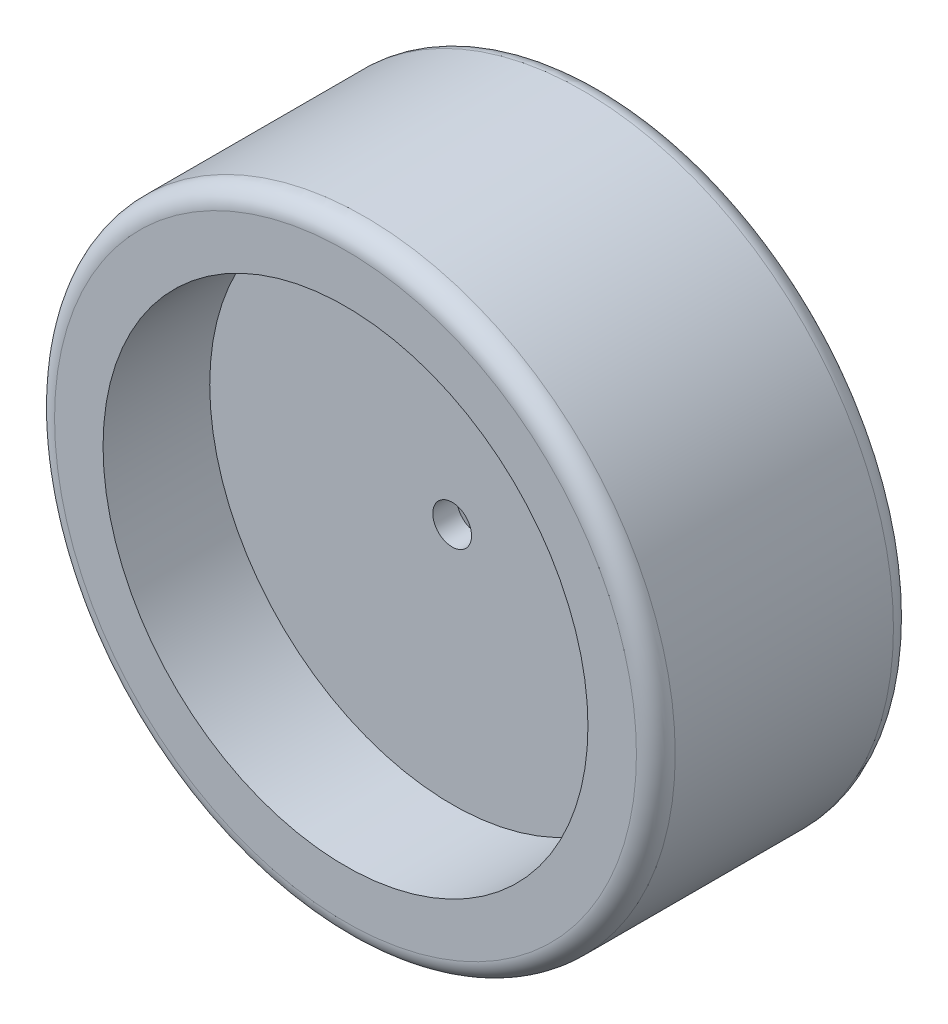
SolidWorks part; units mm, degrees
ref_plane "前视基准面" through (0, 0, 0) normal (0, 0, 1) x (1, 0, 0)
ref_plane "上视基准面" through (0, 0, 0) normal (0, 1, 0) x (1, 0, 0)
ref_plane "右视基准面" through (0, 0, 0) normal (1, 0, 0) x (0, 0, -1)
sketch "草图1" plane through (0, 0, 0) normal (0, 0, 1) x (1, 0, 0)
  line L1 (3.4641, 6) -> (-3.4641, 6)
  line L2 (-3.4641, 6) -> (-6.9282, 0)
  line L3 (-6.9282, 0) -> (-3.4641, -6)
  line L4 (-3.4641, -6) -> (3.4641, -6)
  line L5 (3.4641, -6) -> (6.9282, 0)
  line L6 (6.9282, 0) -> (3.4641, 6)
  circle A2 centre (0, 0) radius 25
extrude "凸台-拉伸1" add sketch "草图1" along normal blind 4 from offset 1
sketch "草图4" plane through (0, 0, 5) normal (0, 0, 1) x (1, 0, 0)
  circle A0 centre (0, 0) radius 25
  circle A1 centre (0, 0) radius 2
extrude "凸台-拉伸3" add sketch "草图4" along normal blind 2.5
sketch "草图6" plane through (0, 0, 7.5) normal (0, 0, 1) x (1, 0, 0)
  circle A0 centre (0, 0) radius 25
  circle A1 centre (0, 0) radius 32
extrude "凸台-拉伸4" add sketch "草图6" against normal blind 26.5 from offset 11
fillet "圆角1" radius 2 2 edges at (32, 0, -8) (32, 0, 18.5)
